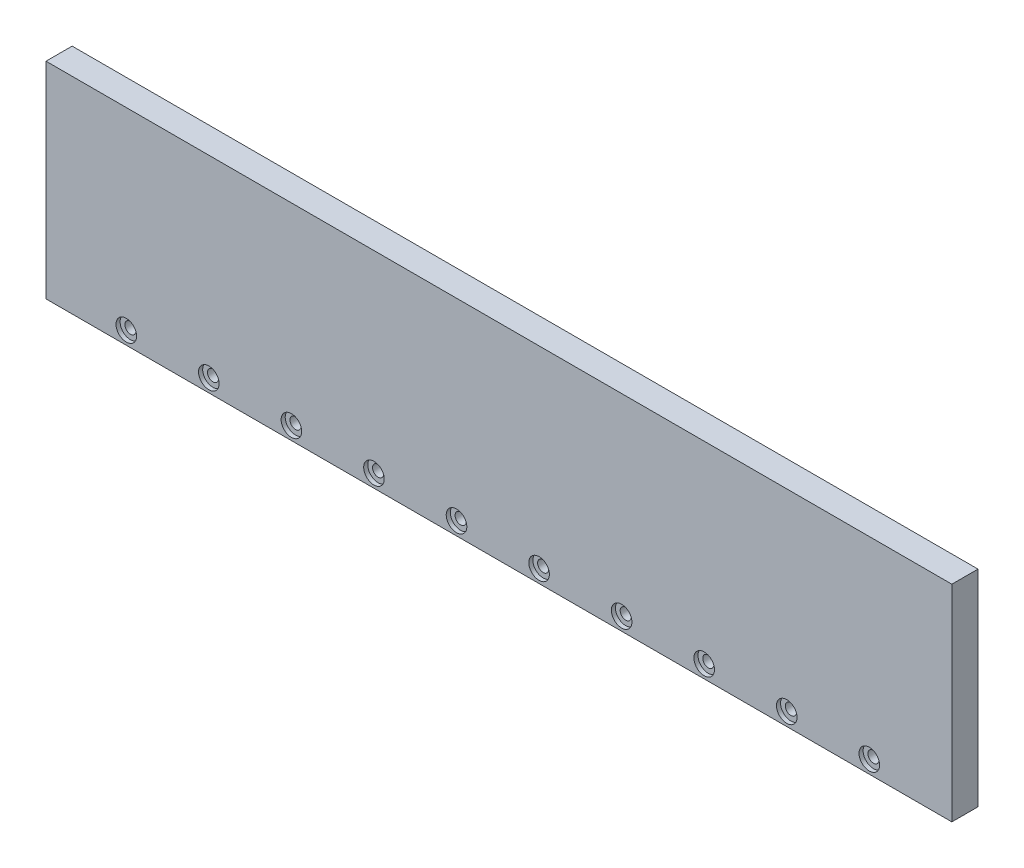
SolidWorks part; units mm, degrees
ref_plane "Front Plane" through (0, 0, 0) normal (0, 0, 1) x (1, 0, 0)
ref_plane "Top Plane" through (0, 0, 0) normal (0, 1, 0) x (1, 0, 0)
ref_plane "Right Plane" through (0, 0, 0) normal (1, 0, 0) x (0, 0, -1)
sketch "Sketch1" plane through (0, 0, 0) normal (0, 0, 1) x (1, 0, 0)
  line L1 (-110, -25) -> (110, -25)
  line L2 (-110, -25) -> (-110, 25)
  line L3 (-110, 25) -> (110, 25)
  line L4 (110, -25) -> (110, 25)
  line L5 (-110, -25) -> (110, 25) construction
  line L6 (-110, 25) -> (110, -25) construction
  point P0 (0, 0)
  dimension "D1" = 220
  dimension "D2" = 50
extrude "Boss-Extrude1" add sketch "Sketch1" along normal mid plane 6.35
hole_wizard "CBORE for M2.5 SHCS1" positions "Sketch2" profile "Sketch3" counterbore size "M2.5" standard "ANSI Metric"
sketch "Sketch2" plane through (0, 0, 3.175) normal (0, 0, 1) x (1, 0, 0)
  line L0 (-110, -25) -> (110, -25) construction
  line L1 (110, -25) -> (110, 25) construction
  line L2 (110, -21.825) -> (89.95, -21.825) construction
  line L3 (89.95, -21.825) -> (69.9, -21.825) construction
  line L4 (69.9, -21.825) -> (49.85, -21.825) construction
  line L5 (49.85, -21.825) -> (29.8, -21.825) construction
  line L6 (29.8, -21.825) -> (9.75, -21.825) construction
  line L7 (9.75, -21.825) -> (-10.3, -21.825) construction
  line L8 (-10.3, -21.825) -> (-30.35, -21.825) construction
  line L9 (-30.35, -21.825) -> (-50.4, -21.825) construction
  line L10 (-50.4, -21.825) -> (-70.45, -21.825) construction
  line L11 (-70.45, -21.825) -> (-90.5, -21.825) construction
  point P0 (89.95, -21.825)
  point P10 (69.9, -21.825)
  point P12 (49.85, -21.825)
  point P14 (29.8, -21.825)
  point P16 (9.75, -21.825)
  point P18 (-10.3, -21.825)
  point P20 (-30.35, -21.825)
  point P22 (-50.4, -21.825)
  point P24 (-70.45, -21.825)
  point P26 (-90.5, -21.825)
  dimension "D1" = 3.175
  dimension "D2" = 20.05
sketch "Sketch3" plane through (89.95, -21.825, 3.175) normal (1, 0, 0) x (0, -1, 0)
  line L0 (0, 0) -> (0, 15.8112)
  line L1 (0, 15.8112) -> (1.35, 15)
  line L2 (1.35, 15) -> (1.35, 1)
  line L3 (1.35, 1) -> (2.5, 1)
  line L4 (2.5, 1) -> (2.5, 0)
  line L5 (2.5, 0) -> (0, 0)
  line L10 (0, 15.8112) -> (-1.35, 15) construction
  line L11 (0, -6.35) -> (0, 107.95) construction
  dimension "Hole Dia." = 2.7
  dimension "Hole Depth" = 15
  dimension "C'Bore Dia." = 5
  dimension "C'Bore Depth" = 1
  dimension "Drill Angle" = 118
